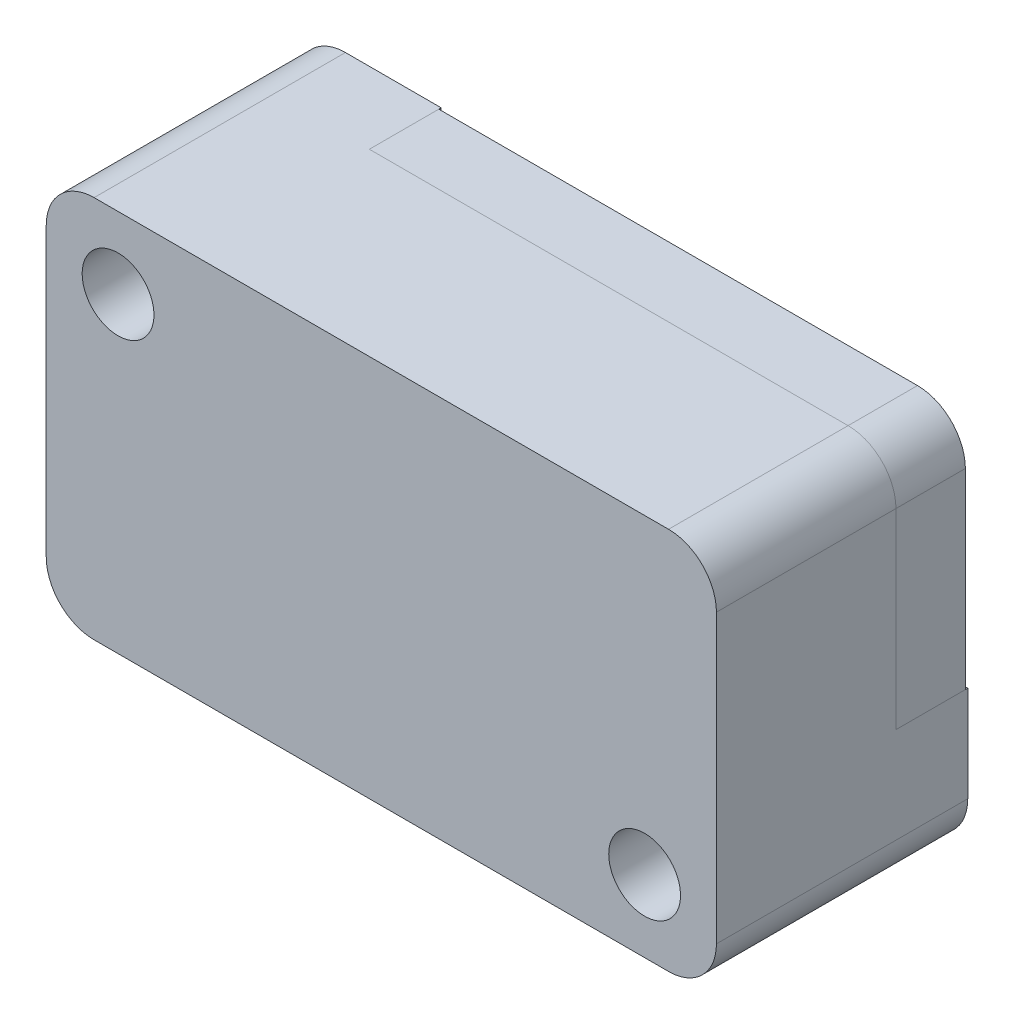
SolidWorks part; units mm, degrees
ref_plane "Front Plane" through (0, 0, 0) normal (0, 0, 1) x (1, 0, 0)
ref_plane "Top Plane" through (0, 0, 0) normal (0, 1, 0) x (1, 0, 0)
ref_plane "Right Plane" through (0, 0, 0) normal (1, 0, 0) x (0, 0, -1)
sketch "Sketch1" plane through (0, 0, 0) normal (0, 0, 1) x (1, 0, 0)
  line L0 (11, -5) -> (-11, 5) construction
  line L1 (-14, -8) -> (14, -8)
  line L2 (-14, -8) -> (-14, 8)
  line L3 (-14, 8) -> (14, 8)
  line L4 (14, -8) -> (14, 8)
  line L5 (-14, -8) -> (14, 8) construction
  line L6 (-14, 8) -> (14, -8) construction
  circle A0 centre (-11, 5) radius 1.5
  circle A1 centre (11, -5) radius 1.5
  point P0 (0, 0)
  point P9 (0, 0)
  dimension "D3" = 3
  dimension "D1" = 16
  dimension "D2" = 28
  dimension "D4" = 10
  dimension "D5" = 22
extrude "Boss-Extrude1" add sketch "Sketch1" along normal blind 10.5
fillet "Fillet1" radius 2 4 edges at (14, -8, 5.25) (14, 8, 5.25) (-14, -8, 5.25) (-14, 8, 5.25)
sketch "Sketch3" plane through (0, 0, 0) normal (0, 0, -1) x (-1, 0, 0)
  line L0 (-14, -2) -> (-10, -2)
  line L1 (-14, -6) -> (-14, 6) construction
  line L2 (-8, -4) -> (-8, -8)
  line L3 (12, -8) -> (-12, -8) construction
  line L4 (8, 8) -> (8, 4)
  line L5 (-12, 8) -> (12, 8) construction
  line L6 (10, 2) -> (14, 2)
  line L7 (14, 6) -> (14, -6) construction
  line L8 (-10, -4) -> (-12, -6) construction
  line L9 (-14, -2) -> (-14, 6)
  line L10 (-12, 8) -> (8, 8)
  line L11 (14, 2) -> (14, -6)
  line L12 (12, -8) -> (-8, -8)
  arc A0 (-10, -2) -> (-8, -4) centre (-10, -4) cw
  arc A1 (8, 4) -> (10, 2) centre (10, 4) ccw
  circle A2 centre (-11, -5) radius 1.5 construction
  circle A3 centre (-11, -5) radius 1.5 construction
  arc A4 (-14, -6) -> (-12, -8) centre (-12, -6) ccw construction
  arc A5 (-14, -6) -> (-12, -8) centre (-12, -6) ccw construction
  arc A6 (-12, 8) -> (-14, 6) centre (-12, 6) ccw construction
  arc A7 (-14, 6) -> (-12, 8) centre (-12, 6) cw
  arc A8 (14, -6) -> (12, -8) centre (12, -6) cw
  point P27 (-11, -5)
extrude "Cut-Extrude1" cut sketch "Sketch3" against normal blind 3
sketch "Sketch5" plane through (0, 0, 3) normal (0, 0, -1) x (-1, 0, 0)
  line L8 (-14, 6) -> (-14, -2)
  line L9 (-14, -2) -> (-10, -2)
  line L10 (-8, -4) -> (-8, -8)
  line L11 (-8, -8) -> (12, -8)
  line L12 (14, -6) -> (14, 2)
  line L13 (14, 2) -> (10, 2)
  line L14 (8, 4) -> (8, 8)
  line L15 (8, 8) -> (-12, 8)
  line L16 (-14, 6) -> (-14, -2)
  line L17 (-14, -2) -> (-10, -2)
  line L18 (-8, -4) -> (-8, -8)
  line L19 (-8, -8) -> (12, -8)
  line L20 (14, -6) -> (14, 2)
  line L21 (14, 2) -> (10, 2)
  line L22 (8, 4) -> (8, 8)
  line L23 (8, 8) -> (-12, 8)
  arc A4 (-8, -4) -> (-10, -2) centre (-10, -4) ccw
  arc A5 (12, -8) -> (14, -6) centre (12, -6) ccw
  arc A6 (8, 4) -> (10, 2) centre (10, 4) ccw
  arc A7 (-12, 8) -> (-14, 6) centre (-12, 6) ccw
  arc A8 (-8, -4) -> (-10, -2) centre (-10, -4) ccw
  arc A9 (12, -8) -> (14, -6) centre (12, -6) ccw
  arc A10 (8, 4) -> (10, 2) centre (10, 4) ccw
  arc A11 (-12, 8) -> (-14, 6) centre (-12, 6) ccw
  dimension "D1" = 0
extrude "Boss-Extrude2" add sketch "Sketch5" along normal blind 2.9 separate body
